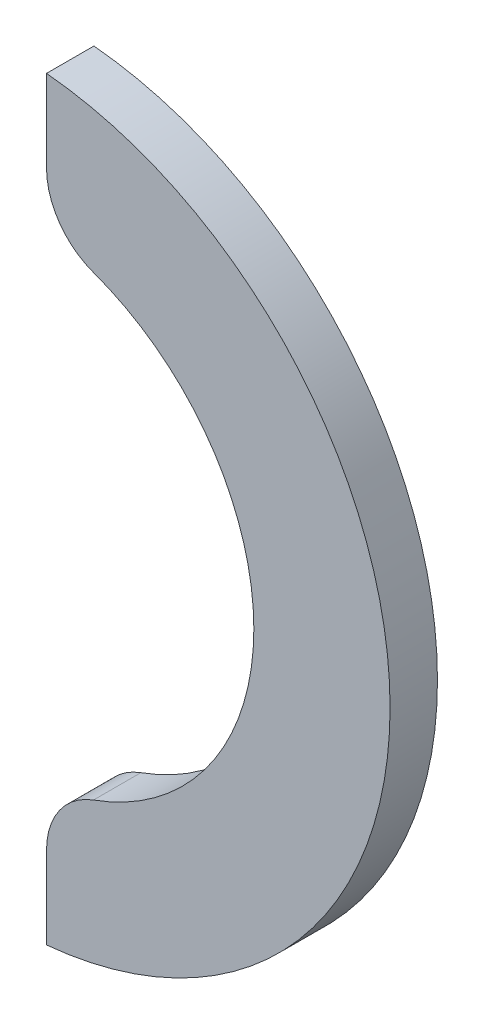
SolidWorks part; units mm, degrees
ref_plane "前视基准面" through (0, 0, 0) normal (0, 0, 1) x (1, 0, 0)
ref_plane "上视基准面" through (0, 0, 0) normal (0, 1, 0) x (1, 0, 0)
ref_plane "右视基准面" through (0, 0, 0) normal (1, 0, 0) x (0, 0, -1)
sketch "草图1" plane through (0, 0, 0) normal (0, 0, 1) x (1, 0, 0)
  circle A0 centre (0, 0) radius 16
  circle A1 centre (0, 0) radius 10.25
  dimension "D1" = 32
  dimension "D2" = 20.5
extrude "凸台-拉伸1" add sketch "草图1" along normal blind 2
sketch "草图2" plane through (0, 0, 2) normal (0, 0, 1) x (1, 0, 0)
  line L0 (1.5, 21.2065) -> (1.5, -27.6644)
  line L1 (0, -1.1) -> (0, 1.1) construction
  dimension "D1" = 1.5
extrude "切除-拉伸1" cut sketch "草图2" against normal through all and the other way through all flip side to cut
fillet "圆角1" radius 3 2 edges at (1.5, -10.1396, 1) (1.5, 10.1396, 1)
